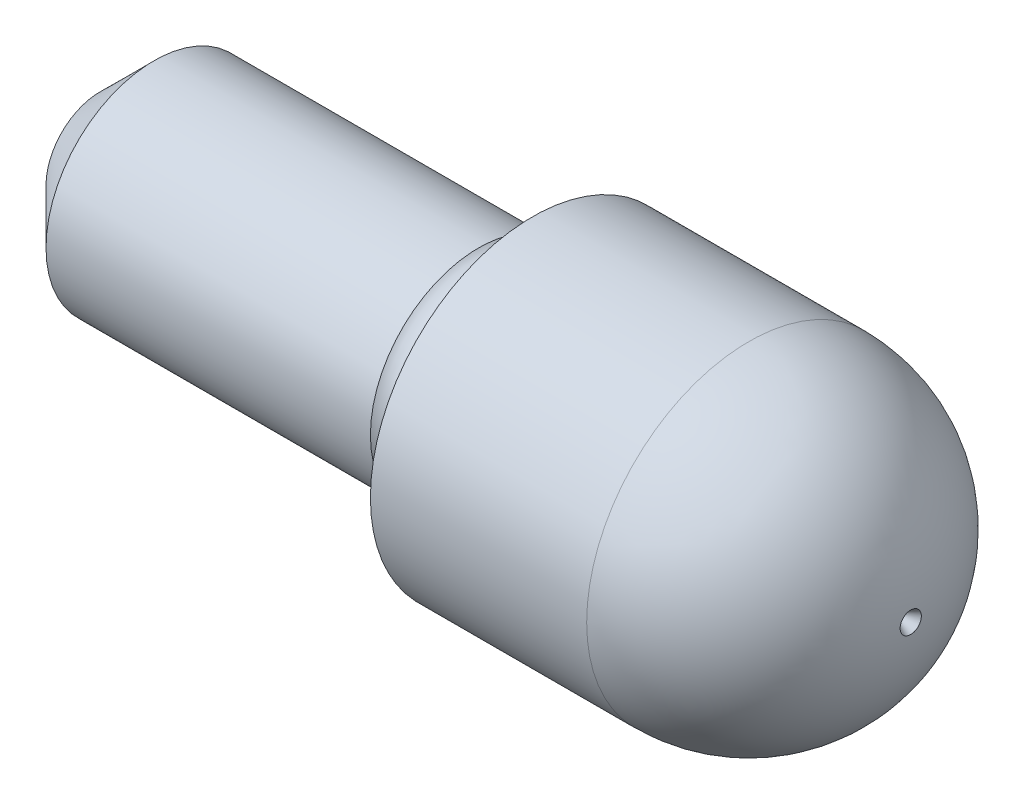
SolidWorks part; units mm, degrees
ref_plane "Front Plane" through (0, 0, 0) normal (0, 0, 1) x (1, 0, 0)
ref_plane "Top Plane" through (0, 0, 0) normal (0, 1, 0) x (1, 0, 0)
ref_plane "Right Plane" through (0, 0, 0) normal (1, 0, 0) x (0, 0, -1)
ref_plane "Plane1" through (0, 0, 0) normal (0, 0, -1) x (-1, 0, 0)
sketch "Sketch1" plane through (0, 0, 0) normal (0, 0, -1) x (-1, 0, 0)
  line L0 (-3.4968, 0.0981) -> (-3.3268, 0)
  line L1 (-3.3268, 0) -> (3.8268, 0)
  line L2 (3.8268, 0) -> (4, 0.1)
  line L3 (4, 0.1) -> (4, 0.5)
  line L4 (4, 0.5) -> (3.5, 1)
  line L5 (3.5, 1) -> (0.5, 1)
  line L6 (0.3677, 0.95) -> (0.2, 0.95)
  line L7 (0, 1.15) -> (0, 1.5)
  line L8 (0, 1.5) -> (-2, 1.5)
  line L9 (-3.5015, 0) -> (4, 0) construction
  arc A0 (0.5, 1) -> (0.3677, 0.95) centre (0.3677, 1.15) cw
  arc A1 (0.2, 0.95) -> (0, 1.15) centre (0.2, 1.15) cw
  arc A2 (-2, 1.5) -> (-3.4968, 0.0981) centre (-2, 0) ccw
revolve "Revolve1" add sketch "Sketch1" angle 360 about L9
